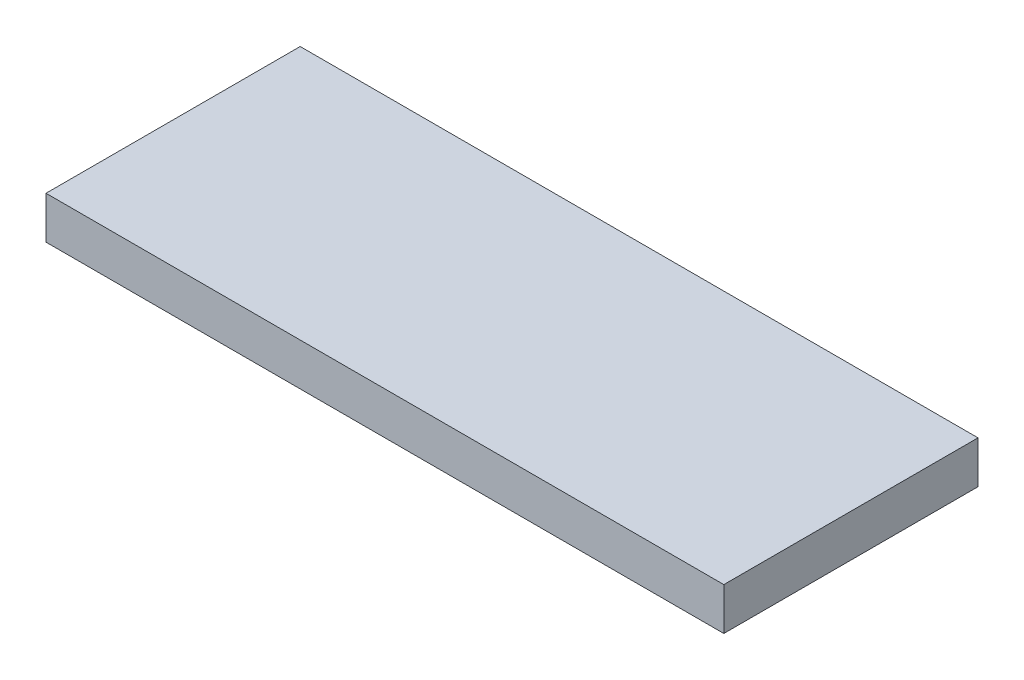
SolidWorks part; units mm, degrees
material "Brass"
ref_plane "Front Plane" through (0, 0, 0) normal (0, 0, 1) x (1, 0, 0)
ref_plane "Top Plane" through (0, 0, 0) normal (0, 1, 0) x (1, 0, 0)
ref_plane "Right Plane" through (0, 0, 0) normal (1, 0, 0) x (0, 0, -1)
sketch "Sketch1" plane through (0, 0, 0) normal (0, 1, 0) x (1, 0, 0)
  line L1 (-80, 30) -> (80, 30)
  line L2 (-80, 30) -> (-80, -30)
  line L3 (-80, -30) -> (80, -30)
  line L4 (80, 30) -> (80, -30)
  line L5 (0, -30) -> (0, 30) construction
  line L6 (-80, 0) -> (80, 0) construction
  point P0 (0, 0)
extrude "Boss-Extrude1" add sketch "Sketch1" along normal blind 10
